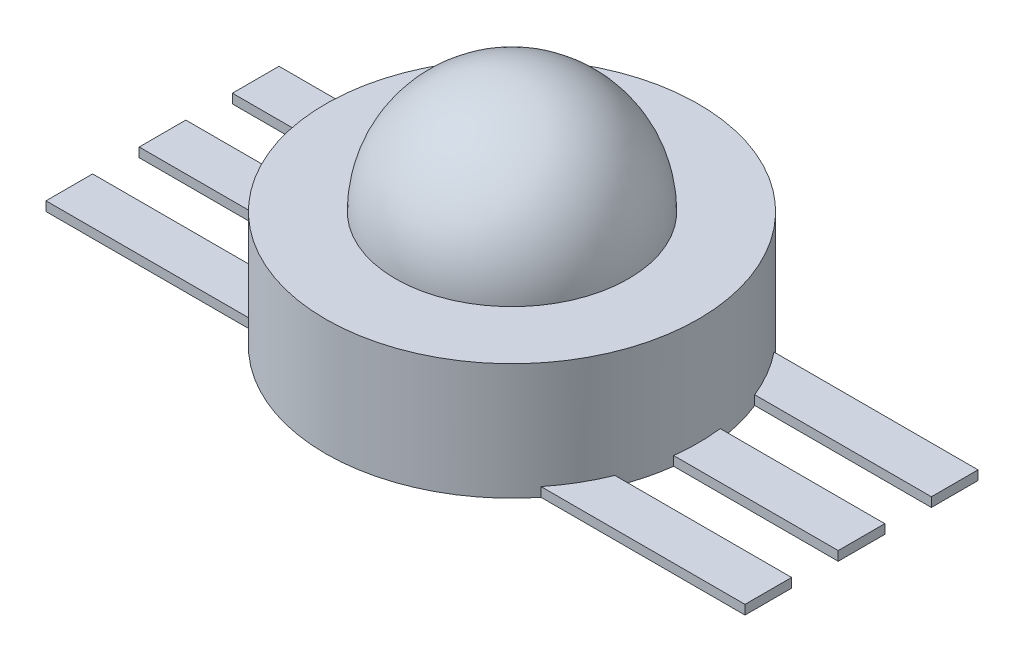
SolidWorks part; units mm, degrees
ref_plane "Спереди" through (0, 0, 0) normal (0, 0, 1) x (1, 0, 0)
ref_plane "Сверху" through (0, 0, 0) normal (0, 1, 0) x (1, 0, 0)
ref_plane "Справа" through (0, 0, 0) normal (1, 0, 0) x (0, 0, -1)
sketch "Эскиз1" plane through (0, 0, 0) normal (0, 1, 0) x (1, 0, 0)
  circle A0 centre (0, 0) radius 4
  dimension "D1" = 8
extrude "Бобышка-Вытянуть1" add sketch "Эскиз1" along normal blind 2.5
sketch "Эскиз2" plane through (0, 0, 0) normal (0, 0, 1) x (1, 0, 0)
  line L0 (4, 2.5) -> (-4, 2.5) construction
  line L1 (0, 0) -> (0, 5) construction
  line L2 (-2.5, 2.5) -> (0, 2.5)
  line L3 (0, 2.5) -> (0, 5)
  arc A0 (-2.5, 2.5) -> (0, 5) centre (0, 2.5) cw
  dimension "D1" = 5
revolve "Повернуть1" add sketch "Эскиз2" angle 360 about L1
sketch "Эскиз3" plane through (0, 0, 0) normal (0, 1, 0) x (1, 0, 0)
  line L0 (0, 2.5) -> (0, -2.5) construction
  line L1 (-7.5, 2.5) -> (7.5, 2.5)
  line L2 (-7.5, 2.5) -> (-7.5, 1.5)
  line L3 (-7.5, 1.5) -> (7.5, 1.5)
  line L4 (7.5, 2.5) -> (7.5, 1.5)
  line L5 (-7.5, 0) -> (7.5, 0) construction
  line L6 (-7.5, 0.5) -> (7.5, 0.5)
  line L7 (-7.5, 0.5) -> (-7.5, -0.5)
  line L8 (-7.5, -0.5) -> (7.5, -0.5)
  line L9 (7.5, 0.5) -> (7.5, -0.5)
  line L10 (7.5, -2.5) -> (7.5, -1.5)
  line L11 (-7.5, -1.5) -> (7.5, -1.5)
  line L12 (-7.5, -2.5) -> (-7.5, -1.5)
  line L13 (-7.5, -2.5) -> (7.5, -2.5)
  point P17 (0, 0)
  dimension "D1" = 15
  dimension "D2" = 5
  dimension "D3" = 1
extrude "Бобышка-Вытянуть2" add sketch "Эскиз3" along normal blind 0.2
